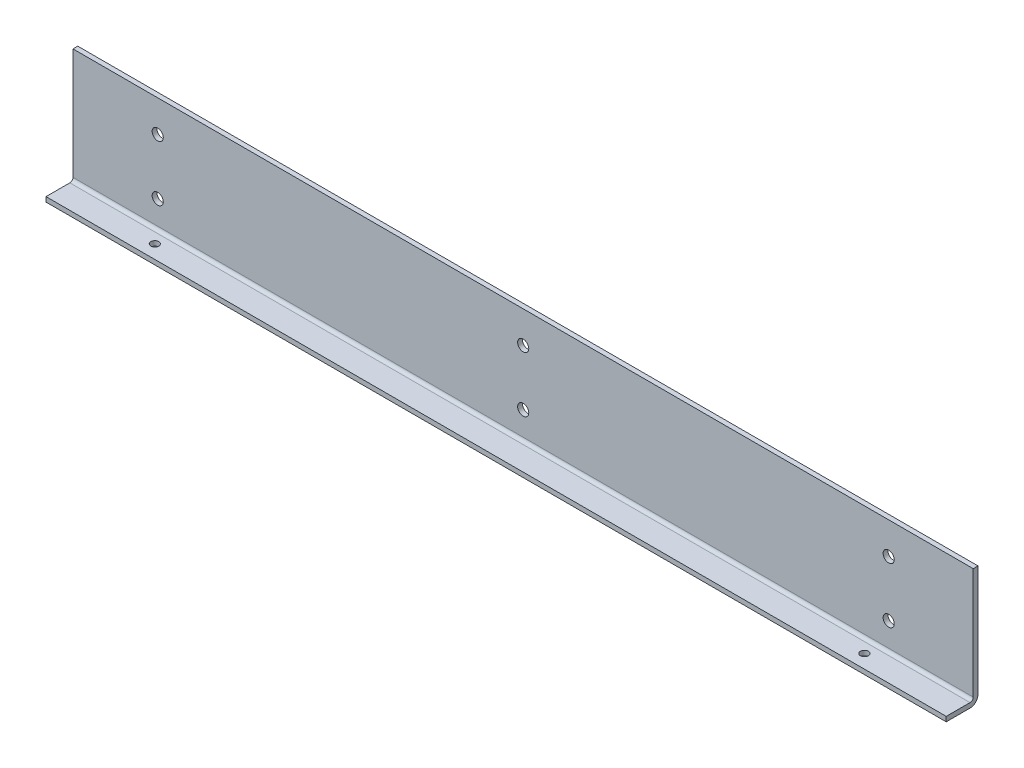
SolidWorks part; units mm, degrees
ref_plane "정면" through (0, 0, 0) normal (0, 0, 1) x (1, 0, 0)
ref_plane "윗면" through (0, 0, 0) normal (0, 1, 0) x (1, 0, 0)
ref_plane "우측면" through (0, 0, 0) normal (1, 0, 0) x (0, 0, -1)
sketch "스케치1" plane through (0, 0, 0) normal (0, 0, 1) x (1, 0, 0)
  line L1 (0, 0) -> (566.5, 0)
  line L2 (0, 0) -> (0, 75)
  line L3 (0, 75) -> (566.5, 75)
  line L4 (566.5, 0) -> (566.5, 75)
  dimension "D1" = 566.5
  dimension "D2" = 75
extrude "보스-돌출1" add sketch "스케치1" along normal blind 3
sketch "스케치2" plane through (0, 0, 3) normal (0, 0, 1) x (1, 0, 0)
  line L0 (566.5, 0) -> (566.5, 75) construction
  line L1 (0, 0) -> (566.5, 0)
  line L2 (0, 0) -> (0, 3)
  line L3 (0, 3) -> (566.5, 3)
  line L4 (566.5, 0) -> (566.5, 3)
  dimension "D1" = 3
extrude "보스-돌출2" add sketch "스케치2" along normal blind 17
sketch "스케치3" plane through (0, 0, 3) normal (0, 0, 1) x (1, 0, 0)
  line L0 (0, 0) -> (566.5, 0) construction
  line L1 (0, 75) -> (0, 3) construction
  circle A0 centre (53.3, 55) radius 3.5
  circle A1 centre (53.3, 20) radius 3.5
  circle A2 centre (283.3, 55) radius 3.5
  circle A3 centre (283.3, 20) radius 3.5
  circle A4 centre (513.3, 55) radius 3.5
  circle A5 centre (513.3, 20) radius 3.5
  dimension "D6" = 7
  dimension "D1" = 20
  dimension "D2" = 35
  dimension "D3" = 53.3
  dimension "D4" = 230
  dimension "D5" = 230
extrude "컷-돌출1" cut sketch "스케치3" against normal through all
sketch "스케치4" plane through (0, 3, 0) normal (0, 1, 0) x (1, 0, 0)
  line L0 (566.5, -20) -> (0, -20) construction
  line L1 (0, -20) -> (0, -3) construction
  circle A0 centre (60, -11.5) radius 2.5
  circle A1 centre (506.5, -11.5) radius 2.5
  dimension "D2" = 5
  dimension "D3" = 5
  dimension "D1" = 8.5
  dimension "D4" = 60
  dimension "D5" = 446.5
extrude "컷-돌출2" cut sketch "스케치4" against normal through all
fillet "필렛2" radius 2 1 edges at (283.25, 3, 3)
fillet "필렛3" radius 5 1 edges at (283.25, 0, 0)
